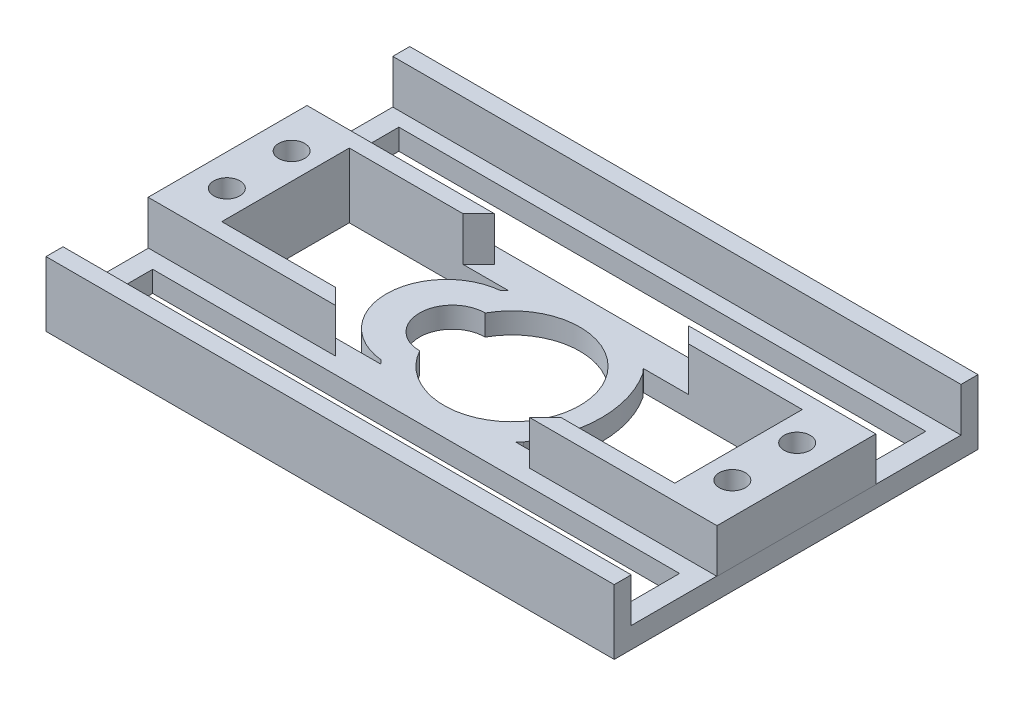
SolidWorks part; units mm, degrees
material "PLA"
ref_plane "Front Plane" through (0, 0, 0) normal (0, 0, 1) x (1, 0, 0)
ref_plane "Top Plane" through (0, 0, 0) normal (0, 1, 0) x (1, 0, 0)
ref_plane "Right Plane" through (0, 0, 0) normal (1, 0, 0) x (0, 0, -1)
sketch "Sketch1" plane through (0, 0, 0) normal (0, 1, 0) x (1, 0, 0)
  line L0 (27.178, 17.399) -> (27.178, 14.399) construction
  line L1 (-27.178, -17.399) -> (27.178, -17.399)
  line L2 (-27.178, -17.399) -> (-27.178, 17.399)
  line L3 (-27.178, 17.399) -> (27.178, 17.399)
  line L4 (27.178, -17.399) -> (27.178, 17.399)
  line L5 (-27.178, -17.399) -> (27.178, 17.399) construction
  line L6 (-27.178, 17.399) -> (27.178, -17.399) construction
  line L7 (27.178, 14.399) -> (25.178, 14.399) construction
  line L8 (-55, 0) -> (55, 0) construction
  line L9 (25.178, 14.399) -> (-25.222, 14.399)
  line L10 (25.178, 14.399) -> (25.178, 9.149)
  line L11 (25.178, 9.149) -> (-25.222, 9.149)
  line L12 (-25.222, 14.399) -> (-25.222, 9.149)
  line L13 (25.178, -9.149) -> (-25.222, -9.149)
  line L14 (25.178, -14.399) -> (-25.222, -14.399)
  line L15 (25.178, -14.399) -> (25.178, -9.149)
  line L16 (-25.222, -14.399) -> (-25.222, -9.149)
  line L17 (25.178, 14.399) -> (25.178, 4.3363) construction
  line L18 (25.178, 4.3363) -> (24.3559, 4.3363) construction
  line L19 (24.3559, 4.3363) -> (24.3559, 3.099) construction
  line L20 (24.3559, 3.099) -> (25.428, 3.099) construction
  line L21 (25.428, 3.099) -> (25.428, 2.7468) construction
  line L22 (25.428, 2.7468) -> (22.9786, 2.7468) construction
  line L23 (0, -55) -> (0, 55) construction
  circle A1 centre (24.178, 3.099) radius 1.25
  circle A2 centre (24.178, -3.099) radius 1.25
  circle A3 centre (-24.178, -3.099) radius 1.25
  circle A4 centre (-24.178, 3.099) radius 1.25
  point P0 (0, 0)
  point P26 (24.178, 3.099)
  dimension "D1" = 54.356
  dimension "D2" = 34.798
  dimension "D3" = 2
  dimension "D4" = 3
  dimension "D5" = 5.25
  dimension "D6" = 50.4
  dimension "D7" = 1.0721
  dimension "D8" = 0.3522
  dimension "D9" = 2.4494
  dimension "D10" = 1.2373
extrude "Boss-Extrude1" add sketch "Sketch1" along normal blind 2
sketch "Sketch2" plane through (0, 2, 0) normal (0, 1, 0) x (1, 0, 0)
  line L4 (-27.178, 15.772) -> (27.178, 15.772)
  line L11 (27.178, -17.399) -> (27.178, 17.399) construction
  line L12 (-27.178, 17.399) -> (-27.178, -17.399) construction
  line L13 (27.178, 17.399) -> (-27.178, 17.399) construction
  line L14 (27.178, 15.772) -> (27.178, 17.399)
  line L15 (-27.178, 17.399) -> (-27.178, 15.772)
  line L16 (27.178, 17.399) -> (-27.178, 17.399)
  line L18 (-55, 0) -> (55, 0) construction
  line L19 (27.178, -17.399) -> (-27.178, -17.399)
  line L20 (-27.178, -17.399) -> (-27.178, -15.772)
  line L21 (27.178, -15.772) -> (27.178, -17.399)
  line L22 (-27.178, -15.772) -> (27.178, -15.772)
  point P8 (0, 0)
  point P9 (0, 0)
extrude "Boss-Extrude2" add sketch "Sketch2" along normal blind 4.2
sketch "Sketch3" plane through (0, 2, 0) normal (0, 1, 0) x (1, 0, 0)
  line L0 (-27.2077, 7.6) -> (-9.2942, 7.6)
  line L1 (-9.2942, 7.6) -> (-10.7999, 6.1)
  line L3 (-9.2942, -7.6) -> (-10.7999, -6.1)
  line L5 (-10.7999, 6.1) -> (-21.666, 6.1)
  line L6 (-21.666, 6.1) -> (-21.666, -6.1)
  line L11 (-55, 0) -> (55, 0) construction
  line L16 (-10.7999, -6.1) -> (-21.666, -6.1)
  line L28 (-27.2077, 7.6) -> (-27.2077, -7.6)
  line L29 (-27.2077, -7.6) -> (-9.2942, -7.6)
  line L30 (0, -55) -> (0, 55) construction
  line L31 (27.2077, -7.6) -> (9.2942, -7.6)
  line L32 (27.2077, 7.6) -> (27.2077, -7.6)
  line L33 (10.7999, -6.1) -> (21.666, -6.1)
  line L34 (21.666, 6.1) -> (21.666, -6.1)
  line L35 (10.7999, 6.1) -> (21.666, 6.1)
  line L36 (9.2942, -7.6) -> (10.7999, -6.1)
  line L37 (9.2942, 7.6) -> (10.7999, 6.1)
  line L38 (27.2077, 7.6) -> (9.2942, 7.6)
  circle A2 centre (-24.178, -3.099) radius 1.25 construction
  circle A3 centre (-24.178, 3.099) radius 1.25 construction
  circle A6 centre (-24.178, -3.099) radius 1.25
  circle A7 centre (-24.178, 3.099) radius 1.25
  circle A8 centre (24.178, 3.099) radius 1.25
  circle A9 centre (24.178, -3.099) radius 1.25
  point P9 (-27.178, 0)
  point P10 (-21.666, 0)
  point P25 (21.666, 0)
  point P26 (27.178, 0)
  dimension "D4" = 10.8661
  dimension "D5" = 12.2
  dimension "D6" = 17.9135
extrude "Boss-Extrude3" add sketch "Sketch3" along normal blind 4.2
sketch "Sketch4" plane through (0, 0, 0) normal (0, -1, 0) x (1, 0, 0)
  line L0 (-6.8177, 5.7235) -> (-12.0031, 5.7235) construction
  line L1 (-12.0031, 5.7235) -> (-12.0031, -0.3852) construction
  line L2 (0, -55) -> (0, 55) construction
  line L8 (-10.7999, 6.1) -> (-21.666, 6.1) construction
  line L9 (-21.666, 6.1) -> (-21.666, -6.1) construction
  line L10 (-21.666, -6.1) -> (-10.7999, -6.1) construction
  line L12 (10.7999, -6.1) -> (6.457, -6.1)
  line L14 (-10.7999, 6.1) -> (-6.457, 6.1)
  line L15 (-6.457, 6.1) -> (-6.8177, 5.7235)
  line L24 (-10.7999, 6.1) -> (-21.666, 6.1)
  line L25 (-21.666, 6.1) -> (-21.666, -6.1)
  line L26 (-21.666, -6.1) -> (-10.7999, -6.1)
  line L32 (6.457, -6.1) -> (6.8177, -5.7235)
  line L33 (55, 0) -> (-55, 0) construction
  line L34 (-6.457, -6.1) -> (-6.8177, -5.7235)
  line L35 (-10.7999, -6.1) -> (-6.457, -6.1)
  line L36 (21.666, -6.1) -> (10.7999, -6.1)
  line L37 (21.666, 6.1) -> (21.666, -6.1)
  line L38 (10.7999, 6.1) -> (21.666, 6.1)
  line L39 (10.7999, 6.1) -> (6.457, 6.1)
  line L40 (6.457, 6.1) -> (6.8177, 5.7235)
  line L41 (0, 0) -> (8.5211, 0) construction
  line L42 (-5.7051, 0) -> (-8.2034, 0) construction
  line L43 (-6.8177, 5.7235) -> (-6.8177, 0) construction
  arc A4 (-5.6941, -3.1349) -> (-5.6941, 3.1349) centre (0, 0) ccw
  arc A5 (-5.6941, 3.1349) -> (-5.6941, -3.1349) centre (-5.7051, 0) ccw
  arc A10 (-6.8177, 5.7235) -> (-6.8177, -5.7235) centre (-6.266, 0) ccw
  arc A12 (6.8177, 5.7235) -> (6.8177, -5.7235) centre (-1.8014, 0) cw
  point P19 (-12.0031, -0.3852)
  point P34 (0, 0)
  point P35 (8.5211, 0.7019)
  dimension "D1" = 10.8661
  dimension "D2" = 4.3429
  dimension "D3" = 0.3607
  dimension "D4" = 0.3765
  dimension "D5" = 5.1854
  dimension "D6" = 6.1086
  dimension "D7" = 8.5211
  dimension "D9" = 12.2
extrude "Cut-Extrude1" cut sketch "Sketch4" against normal through all both and the other way through all contours A4 A5 | A10 L15 L14 L24 L25 L26 L35 L34 | L40 A12 L32 L12 L36 L37 L38 L39
